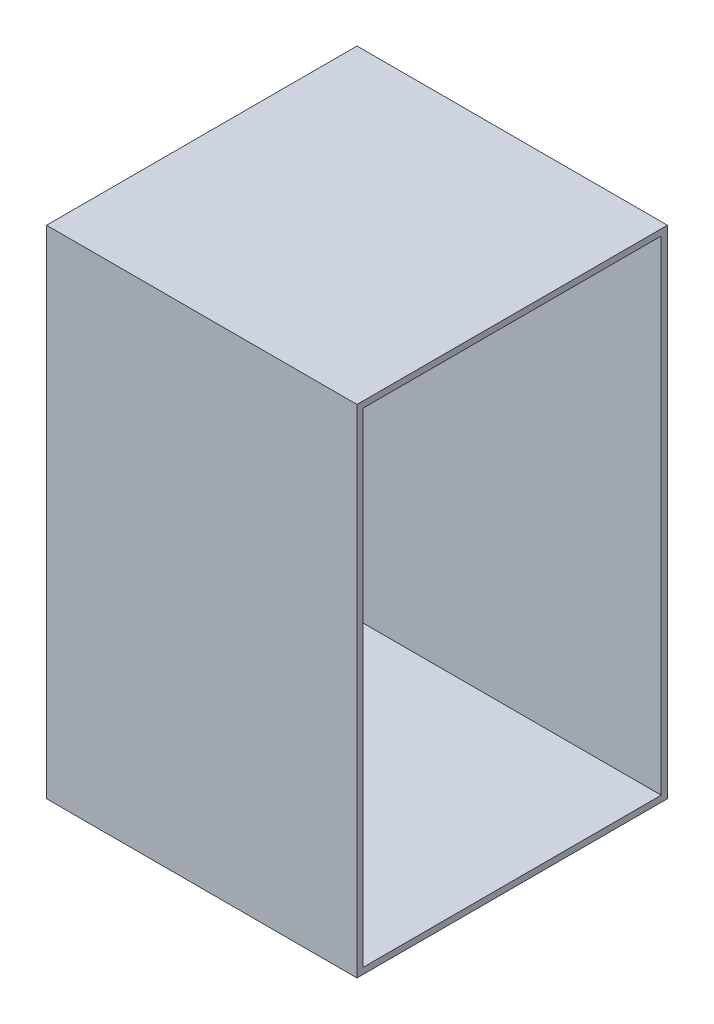
SolidWorks part; units mm, degrees
ref_plane "前视基准面" through (0, 0, 0) normal (0, 0, 1) x (1, 0, 0)
ref_plane "上视基准面" through (0, 0, 0) normal (0, 1, 0) x (1, 0, 0)
ref_plane "右视基准面" through (0, 0, 0) normal (1, 0, 0) x (0, 0, -1)
sketch "草图1" plane through (0, 0, 0) normal (0, 1, 0) x (1, 0, 0)
  line L1 (-250, 250) -> (250, 250)
  line L2 (-250, 250) -> (-250, -250)
  line L3 (-250, -250) -> (250, -250)
  line L4 (250, 250) -> (250, -250)
  point P6 (36.0205, -13.0734)
  point P7 (197.496, 11.7032)
  dimension "D1" = 500
  dimension "D2" = 500
  dimension "D3" = 250
  dimension "D4" = 250
extrude "凸台-拉伸1" add sketch "草图1" along normal mid plane 800
sketch "草图2" plane through (250, 0, 0) normal (1, 0, 0) x (0, 0, -1)
  line L0 (-250, 400) -> (-250, -400) construction
  line L1 (-240, 390) -> (240, 390)
  line L2 (-240, 390) -> (-240, -390)
  line L3 (-240, -390) -> (240, -390)
  line L4 (240, 390) -> (240, -390)
  line L6 (250, 400) -> (250, -400) construction
  line L7 (-250, 400) -> (250, 400) construction
  line L8 (-250, -400) -> (250, -400) construction
  dimension "D1" = 10
  dimension "D2" = 10
  dimension "D3" = 10
  dimension "D4" = 10
extrude "切除-拉伸1" cut sketch "草图2" against normal blind 490
